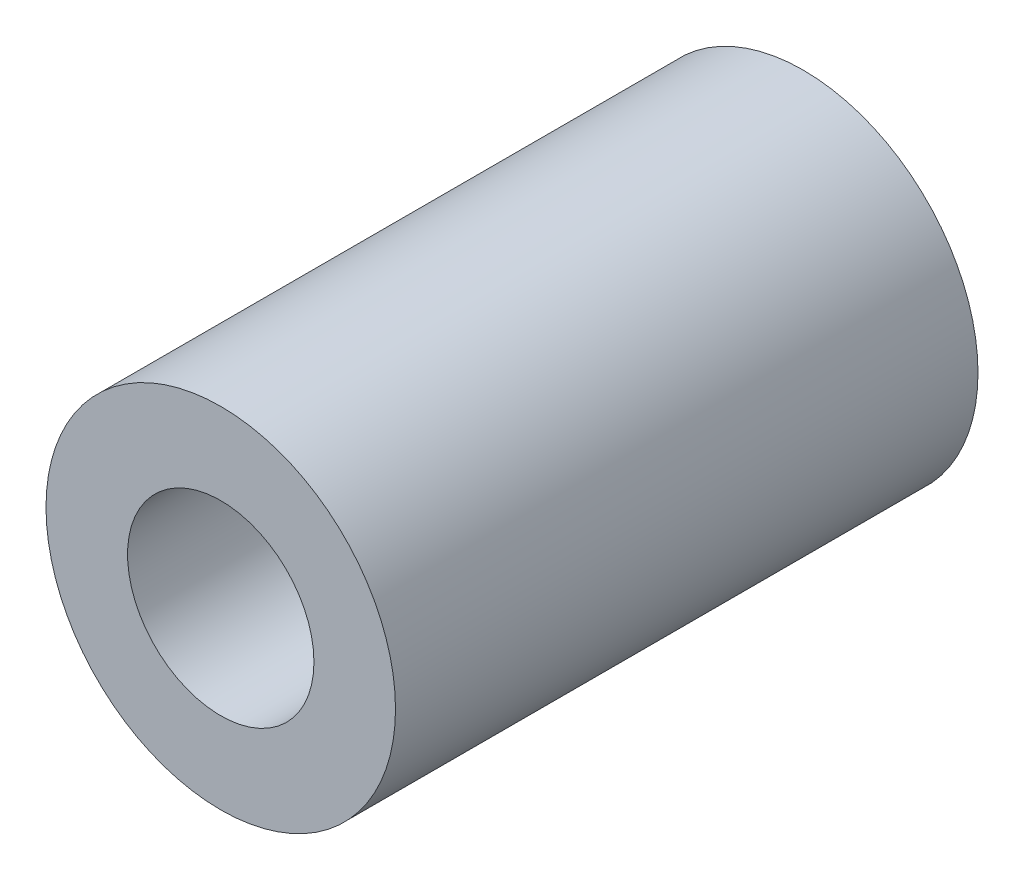
SolidWorks part; units mm, degrees
material "AISI 1015 钢，冷拔 (SS)"
ref_plane "前视基准面" through (0, 0, 0) normal (0, 0, 1) x (1, 0, 0)
ref_plane "上视基准面" through (0, 0, 0) normal (0, 1, 0) x (1, 0, 0)
ref_plane "右视基准面" through (0, 0, 0) normal (1, 0, 0) x (0, 0, -1)
sketch "草图1" plane through (0, 0, 0) normal (0, 0, 1) x (1, 0, 0)
  circle A0 centre (0, 0) radius 7.5
  dimension "D1" = 15
extrude "凸台-拉伸1" add sketch "草图1" along normal mid plane 25
sketch "草图2" plane through (0, 0, -12.5) normal (0, 0, -1) x (-1, 0, 0)
  circle A0 centre (0, 0) radius 3
  dimension "D1" = 6
extrude "切除-拉伸1" cut sketch "草图2" against normal blind 10
sketch "草图3" plane through (0, 0, 12.5) normal (0, 0, 1) x (1, 0, 0)
  circle A0 centre (0, 0) radius 4
  dimension "D1" = 8
extrude "切除-拉伸2" cut sketch "草图3" against normal blind 9
